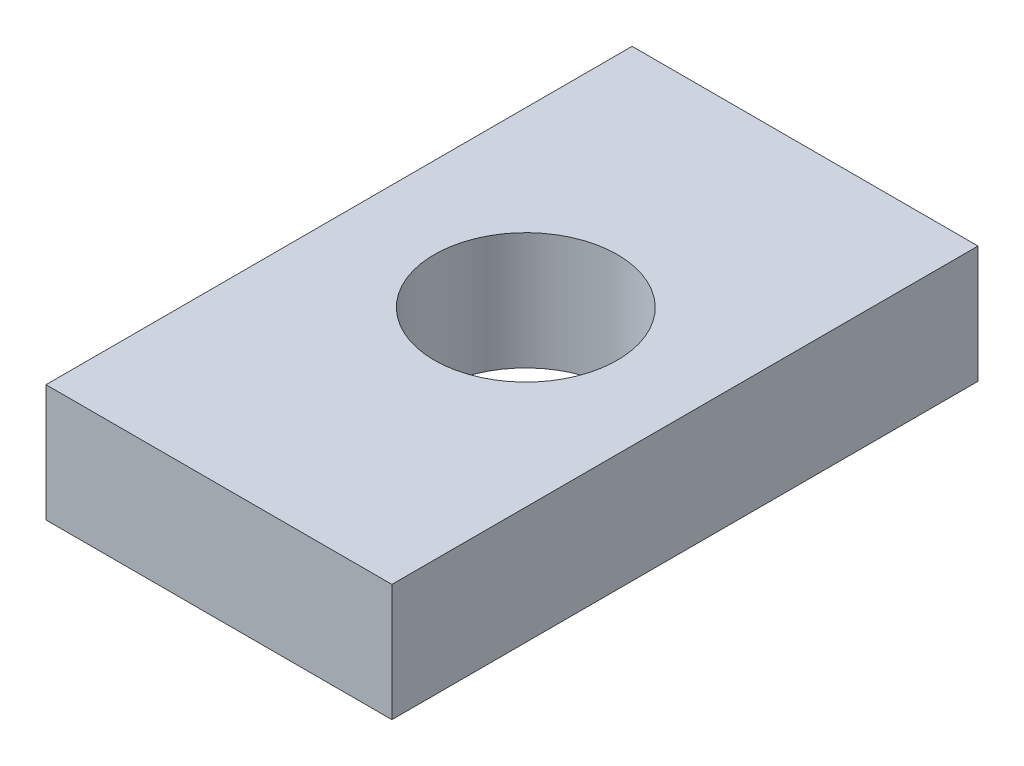
SolidWorks part; units mm, degrees
ref_plane "Front Plane" through (0, 0, 0) normal (0, 0, 1) x (1, 0, 0)
ref_plane "Top Plane" through (0, 0, 0) normal (0, 1, 0) x (1, 0, 0)
ref_plane "Right Plane" through (0, 0, 0) normal (1, 0, 0) x (0, 0, -1)
sketch "Sketch1" plane through (0, 0, 0) normal (0, 1, 0) x (1, 0, 0)
  line L1 (0, 0) -> (29.5209, 0)
  line L2 (0, 0) -> (0, 50.0183)
  line L3 (0, 50.0183) -> (29.5209, 50.0183)
  line L4 (29.5209, 0) -> (29.5209, 50.0183)
extrude "Boss-Extrude1" add sketch "Sketch1" along normal blind 10
sketch "Sketch2" plane through (0, 10, 0) normal (0, 1, 0) x (1, 0, 0)
  circle A0 centre (14.7604, 26.1875) radius 7.8126
extrude "Cut-Extrude1" cut sketch "Sketch2" against normal through all both and the other way through all
